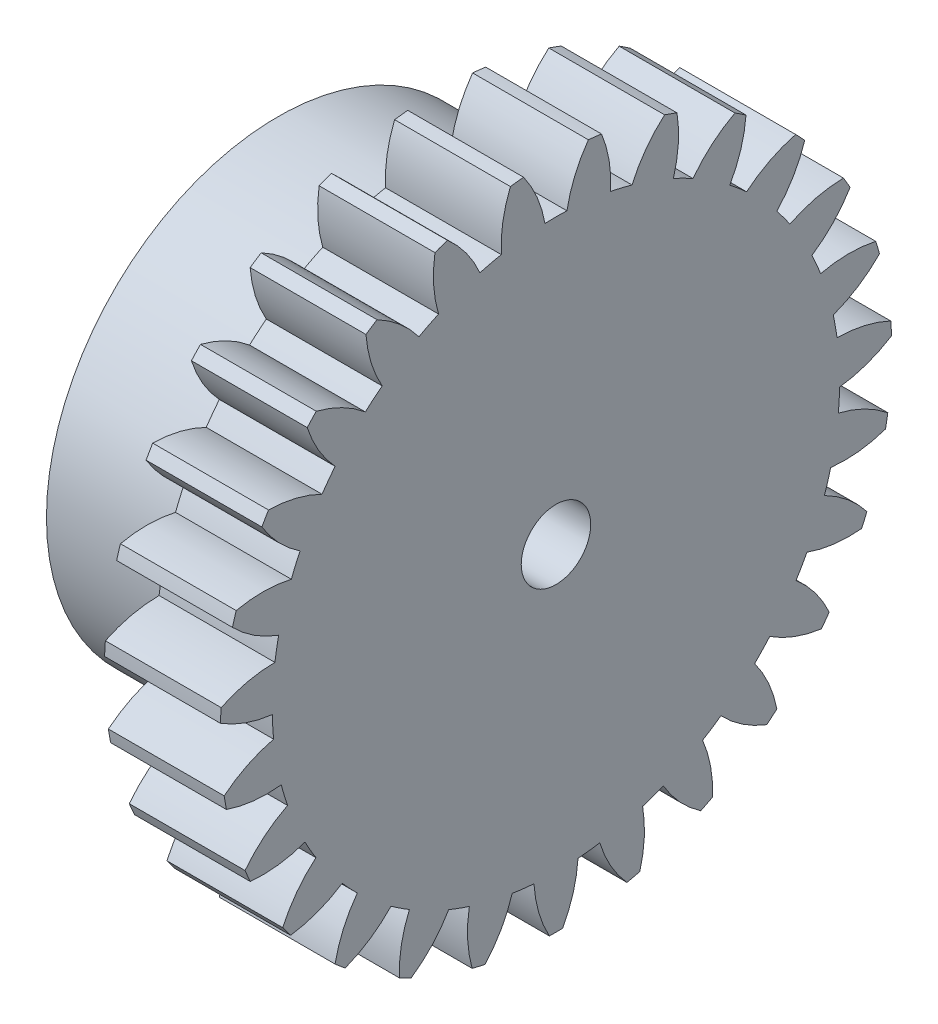
SolidWorks part; units mm, degrees
ref_plane "Plane1" through (0, 0, 0) normal (0, 0, 1) x (1, 0, 0)
ref_plane "Plane2" through (0, 0, 0) normal (0, 1, 0) x (1, 0, 0)
ref_plane "Plane3" through (0, 0, 0) normal (1, 0, 0) x (0, 0, -1)
sketch "HoldingSke" plane through (0, 0, 0) normal (0, 1, 0) x (1, 0, 0)
  line L0 (0, 0) -> (0.891, -0.454)
  line L1 (-15, 0) -> (100, 0) construction
  line L2 (0, 0) -> (-2.1039, 2.3779)
  line L3 (0, 0) -> (-11.863, 4.5341)
  line L4 (0, 0) -> (7.6947, 3.9207)
  line L5 (0, 0) -> (-46.8476, -17.4728)
  line L6 (0, 0) -> (-4.1448, -2.7965)
  line L7 (-2.1039, 2.3779) -> (8.6586, 51.2059)
  line L8 (-76.2, 54.61) -> (-75.7, 54.61)
  line L9 (-71.009, 38.7566) -> (-53.1078, 45.2721)
  line L10 (-76.2, 71.12) -> (104.1128, 71.12)
  line L11 (0, 0) -> (-5, 0)
  line L12 (-76.2, 101.6) -> (-76.162, 101.6)
  line L13 (24.9733, 27.94) -> (52.9518, 28.4284)
  line L14 (24.9733, 27.94) -> (24.9743, 27.94)
  line L15 (24.9733, 27.94) -> (100.4006, 29.5858)
  line L16 (-63.627, -1) -> (-12.827, -1)
  circle A0 centre (0, 0) radius 1.5
  circle A1 centre (0, 0) radius 12.249
  circle A2 centre (0, 0) radius 37.5
  circle A3 centre (0, 0) radius 1.5
  dimension "MHD" = 24.498
  dimension "Hub_dia" = 75
  dimension "Bore" = 3
  dimension "MBD" = 3
  dimension "Num_teeth" = 27
  dimension "Pitch" = 1
  dimension "Overall_len" = 50
  dimension "Show_teeth" = 27
  dimension "Thickness" = 5
  dimension "OAL" = 50.0001
  dimension "T_dim" = 0.5
  dimension "Ap" = 20
  dimension "H" = 19.05
  dimension "Pitch_radius" = 180.3128
  dimension "Width" = 5
  dimension "Backlash" = 0.038
  dimension "Addendum_fac" = 1
  dimension "Dedendum_fac" = 1.25
  dimension "Clearance_fac" = 0.25
  dimension "Dedendum_add" = 0.001
  dimension "Module" = 1
sketch "BasProSke" plane through (0, 0, 0) normal (0, 1, 0) x (1, 0, 0)
  line L0 (-10, 0) -> (60, 0) construction
  line L1 (0, 0) -> (0, 14.5)
  line L2 (0, 0) -> (5, 0)
  line L3 (5, 0) -> (5, 14.5)
  line L4 (5, 14.5) -> (0, 14.5)
  dimension "Thickness" = 5
  dimension "Diameter" = 29
revolve "Base-Revolve" add sketch "BasProSke" angle 360 about L0
sketch "TooCutSke" plane through (0, 0, 0) normal (1, 0, 0) x (0, 0, -1)
  line L1 (0, 0) -> (0, 107) construction
  line L2 (0, 0) -> (-0.8514, 13.4731) construction
  line L3 (0, 0) -> (-3.1301, 26.7794) construction
  line L4 (-0.8514, 13.4731) -> (-1.565, 13.3897) construction
  arc A0 (0.4741, 12.2398) -> (-0.4741, 12.2398) centre (0, 0) ccw
  arc A1 (1.4167, 14.4561) -> (-1.4167, 14.4561) centre (0, 0) ccw
  circle A2 centre (0, 0) radius 13.5 construction
  circle A3 centre (0, 0) radius 12.6859 construction
  arc A4 (-0.4741, 12.2398) -> (-1.4167, 14.4561) centre (-5.7895, 11.2877) ccw
  arc A5 (1.4167, 14.4561) -> (0.4741, 12.2398) centre (5.7895, 11.2877) ccw
  dimension "Root_dia" = 24.498
  dimension "Overcut_dia" = 29.0508
  dimension "Pitch_dia" = 27
  dimension "Base_dia" = 25.3717
  dimension "Flank_rad" = 5.4
  dimension "Half_ang" = 6.667
  dimension "Half_CT" = 0.7185
extrude "ToothCut" cut sketch "TooCutSke" along normal through all
fillet "Breaks" [suppressed] radius 0.02
fillet "RootFillets" [suppressed] radius 0.251
pattern_circular "TeethCuts" count 27 every 13.333 about axis through (-10, 0, 0) along (1, 0, 0) of "ToothCut", "RootFillets", "Breaks"
sketch "HubNeaOneSke" plane through (0, 0, 0) normal (-1, 0, 0) x (0, 0, 1)
  circle A0 centre (0, 0) radius 12.249
  dimension "Diameter" = 24.498
extrude "HubNearOne" [suppressed] add sketch "HubNeaOneSke" along normal blind 45.0001
sketch "HubNeaBotSke" plane through (0, 0, 0) normal (-1, 0, 0) x (0, 0, 1)
  circle A0 centre (0, 0) radius 12.249
  dimension "Diameter" = 24.498
extrude "HubNearBoth" [suppressed] add sketch "HubNeaBotSke" along normal blind 22.5
ref_plane "FarPln" through (5, 0, 0) normal (1, 0, 0) x (0, 0, -1)
sketch "HubFarSke" plane through (5, 0, 0) normal (1, 0, 0) x (0, 0, -1)
  circle A0 centre (0, 0) radius 12.249
  dimension "Diameter" = 24.498
extrude "HubFar" [suppressed] add sketch "HubFarSke" along normal blind 22.5
sketch "BorSke" plane through (0, 0, 0) normal (1, 0, 0) x (0, 0, -1)
  circle A0 centre (0, 0) radius 1.5
  dimension "Diameter" = 3
extrude "Bore" cut sketch "BorSke" along normal mid plane 100.0001
sketch "KeySke" plane through (0, 0, 0) normal (1, 0, 0) x (0, 0, -1)
  line L0 (-0.6, 0) -> (-0.6, 2)
  line L1 (-0.6, 2) -> (0.6, 2)
  line L2 (0.6, 2) -> (0.6, 0)
  line L3 (0, 0) -> (0, 34) construction
  line L4 (-0.6, 0) -> (0.6, 0)
  dimension "Offset" = 2
  dimension "Width" = 1.2
extrude "Keyway" [suppressed] cut sketch "KeySke" along normal mid plane 100.0001
pattern_circular "Keyway2" [suppressed] count 2 every 90 about axis through (-10, 0, 0) along (1, 0, 0)
sketch "Sketch2" plane through (0, 0, 0) normal (-1, 0, 0) x (0, 0, 1)
  circle A0 centre (0, 0) radius 10
  dimension "D1" = 20
extrude "Boss-Extrude1" add sketch "Sketch2" along normal blind 7
sketch "Sketch3" plane through (-7, 0, 0) normal (-1, 0, 0) x (0, 0, 1)
  circle A0 centre (0, 0) radius 1.5
  circle A1 centre (5, 0) radius 1.5
  circle A2 centre (-5, 0) radius 1.5
  dimension "D1" = 5
  dimension "D3" = 3
  dimension "D4" = 3
  dimension "D5" = 3
  dimension "D2" = 5
extrude "Cut-Extrude3" cut sketch "Sketch3" against normal blind 7
equation "' \"Module@HoldingSke\" = 6.35"
equation "' \"Num_teeth@HoldingSke\" = 12"
equation "' \"Ap@HoldingSke\" =  20"
equation "' \"Ap@HoldingSke\" = 20"
equation "' \"Width@HoldingSke\" = 0.5 * 25.4"
equation "' \"Hub_dia@HoldingSke\"= 1 * 25.4"
equation "' \"Hub_dia@HoldingSke\" = 1 * 25.4"
equation "' \"Overall_len@HoldingSke\" = 1.0 * 25.4"
equation "' \"Bore@HoldingSke\" = 0.75 * 25.4"
equation "' \"T_dim@HoldingSke\" = 0.1 * 25.4"
equation "' \"Width@KeySke\" = 0.25 * 25.4"
equation "' \"Show_teeth@HoldingSke\" = 13"
equation "' \"Backlash@HoldingSke\" = 0.009 * 25.4"
equation "' \"Addendum_fac@HoldingSke\" = 1.0"
equation "' \"Dedendum_fac@HoldingSke\" = 1.25"
equation "' \"Dedendum_add@HoldingSke\" = 0.00005 * 25.4"
equation "' \"Clearance_fac@HoldingSke\" = 0.25"
equation "\"Pitch@HoldingSke\" = 1 / \"Module@HoldingSke\""
equation "\"Overcut_dia@TooCutSke\" = (\"Num_teeth@HoldingSke\" + 2 * \"Addendum_fac@HoldingSke\") / \"Pitch@HoldingSke\" + 0.002 * 25.4"
equation "\"Pitch_dia@TooCutSke\" = \"Num_teeth@HoldingSke\" / \"Pitch@HoldingSke\""
equation "\"Base_dia@TooCutSke\" = \"Num_teeth@HoldingSke\" / \"Pitch@HoldingSke\" * cos((\"Ap@HoldingSke\"  * 3.14159265 / 180))"
equation "\"Root_dia@TooCutSke\" = (\"Num_teeth@HoldingSke\" + 2) / \"Pitch@HoldingSke\" - 2 * (\"Addendum_fac@HoldingSke\" + \"Dedendum_fac@HoldingSke\") / \"Pitch@HoldingSke\" - \"Dedendum_add@HoldingSke\" * 2"
equation "\"Half_ang@TooCutSke\" = 180 / \"Num_teeth@HoldingSke\""
equation "\"Half_CT@TooCutSke\" = \"Num_teeth@HoldingSke\" / \"Pitch@HoldingSke\" * sin((3.14159265 / 2 / \"Num_teeth@HoldingSke\")) / 2 - 7 * \"Backlash@HoldingSke\" / 4"
equation "\"Flank_rad@TooCutSke\" = \"Num_teeth@HoldingSke\" / \"Pitch@HoldingSke\" / 5"
equation "\"Radius@RootFillets\" = \"Clearance_fac@HoldingSke\" / \"Pitch@HoldingSke\" + \"Dedendum_add@HoldingSke\""
equation "\"Break_rad@Breaks\" = 0.02 / \"Pitch@HoldingSke\""
equation "\"Thickness@HoldingSke\" = \"Width@HoldingSke\""
equation "\"OAL@HoldingSke\" = \"Thickness@HoldingSke\""
equation "\"MHD@HoldingSke\" = (\"Num_teeth@HoldingSke\" + 2) / \"Pitch@HoldingSke\" - 2 * (\"Addendum_fac@HoldingSke\" + \"Dedendum_fac@HoldingSke\")  / \"Pitch@HoldingSke\" - \"Dedendum_add@HoldingSke\" * 2"
equation "\"MBD@HoldingSke\" = (\"Num_teeth@HoldingSke\" + 2) / \"Pitch@HoldingSke\" - 2 * (\"Addendum_fac@HoldingSke\" + \"Dedendum_fac@HoldingSke\")  / \"Pitch@HoldingSke\" - \"Dedendum_add@HoldingSke\" * 2 - 0.002 * 25.4"
equation "\"MHD@HoldingSke\" = ((sgn( \"MHD@HoldingSke\" - \"Hub_dia@HoldingSke\" )-1)*( \"MHD@HoldingSke\" - \"Hub_dia@HoldingSke\" ))/-2+ \"Hub_dia@HoldingSke\""
equation "\"MBD@HoldingSke\" = ((sgn( \"MBD@HoldingSke\" - \"Bore@HoldingSke\" )-1)*( \"MBD@HoldingSke\" - \"Bore@HoldingSke\" ))/-2+ \"Bore@HoldingSke\""
equation "\"OAL@HoldingSke\" = ((sgn( \"OAL@HoldingSke\" - \"Overall_len@HoldingSke\" )+1)*( \"OAL@HoldingSke\" - \"Overall_len@HoldingSke\" ))/2 + \"Overall_len@HoldingSke\" + 0.000002 * 25.4"
equation "\"Num_teeth@TeethCuts\" = int( \"Show_teeth@HoldingSke\" ) + 1"
equation "\"Num_teeth@TeethCuts\" = ((sgn( \"Num_teeth@TeethCuts\" - \"Num_teeth@HoldingSke\" )-1)*( \"Num_teeth@TeethCuts\" - \"Num_teeth@HoldingSke\" ))/-2+ \"Num_teeth@HoldingSke\""
equation "\"Num_teeth@TeethCuts\" = ((sgn( \"Num_teeth@TeethCuts\" - 2.0)+1)*( \"Num_teeth@TeethCuts\" - 2.0))/2 +2.0"
equation "\"Angle@TeethCuts\" = 360.0 / \"Num_teeth@HoldingSke\""
equation "\"Diameter@BasProSke\" = (\"Num_teeth@HoldingSke\" + 2 * \"Addendum_fac@HoldingSke\") / \"Pitch@HoldingSke\""
equation "\"Thickness@BasProSke\"  = \"Thickness@HoldingSke\""
equation "' \"Fillet_rad@BasProSke\" =  \"Thickness@HoldingSke\" * 0.05"
equation "' \"Fillet_rad@BasProSke\" = \"Thickness@HoldingSke\" * 0.05"
equation "\"MHD@HoldingSke\" = ((sgn( \"MHD@HoldingSke\" - \"Root_dia@TooCutSke\" )-1)*( \"MHD@HoldingSke\" - \"Root_dia@TooCutSke\" ))/-2+ \"Root_dia@TooCutSke\""
equation "\"Diameter@HubNeaOneSke\" = \"MHD@HoldingSke\""
equation "\"Length@HubNearOne\" = \"OAL@HoldingSke\" - \"Thickness@BasProSke\""
equation "\"Diameter@HubNeaBotSke\" = \"MHD@HoldingSke\""
equation "\"Length@HubNearBoth\" = ( \"OAL@HoldingSke\" - \"Thickness@BasProSke\" ) / 2.0"
equation "\"Thickness@FarPln\" = \"Thickness@BasProSke\""
equation "\"Diameter@HubFarSke\" = \"MHD@HoldingSke\""
equation "\"Length@HubFar\" = ( \"OAL@HoldingSke\" - \"Thickness@BasProSke\" ) / 2.0"
equation "\"Diameter@BorSke\" = \"MBD@HoldingSke\""
equation "\"D1@Bore\" = \"OAL@HoldingSke\" * 2.0"
equation "\"D1@Keyway\" = \"OAL@HoldingSke\" * 2.0"
equation "\"Offset@KeySke\" = \"T_dim@HoldingSke\" + \"MBD@HoldingSke\" / 2.0"
